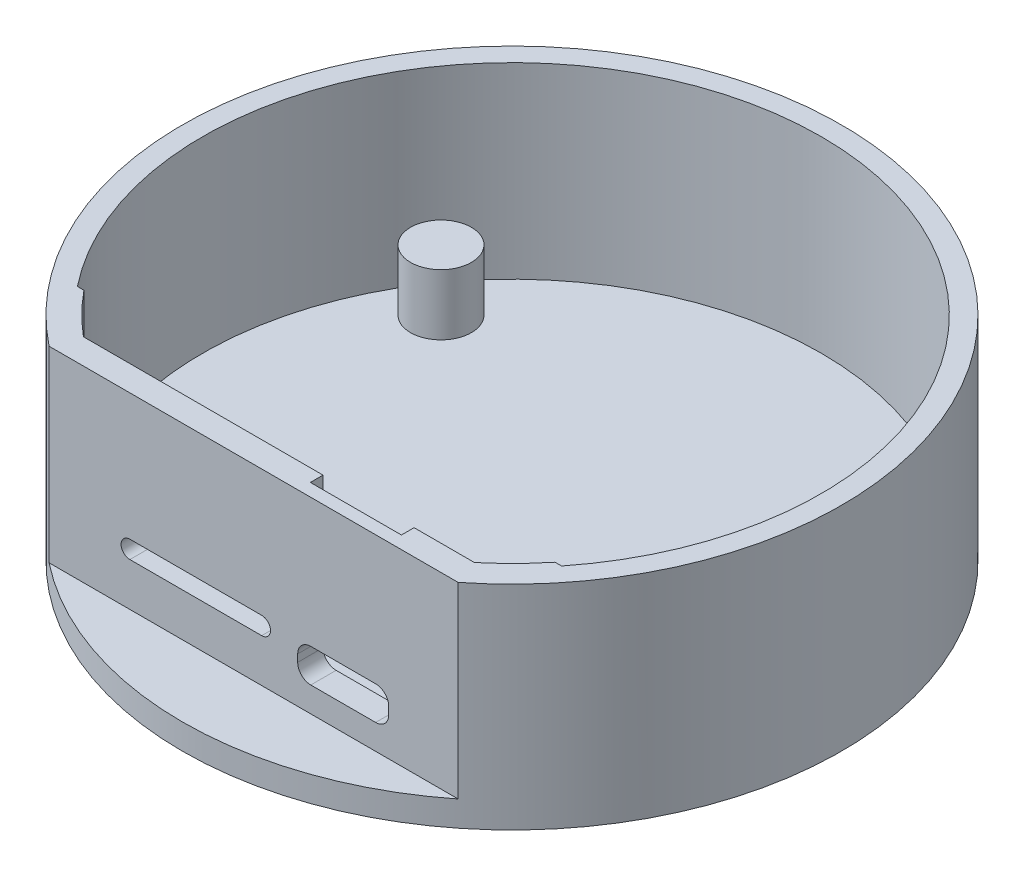
SolidWorks part; units mm, degrees
ref_plane "Front Plane" through (0, 0, 0) normal (0, 0, 1) x (1, 0, 0)
ref_plane "Top Plane" through (0, 0, 0) normal (0, 1, 0) x (1, 0, 0)
ref_plane "Right Plane" through (0, 0, 0) normal (1, 0, 0) x (0, 0, -1)
sketch "Sketch1" plane through (0, 0, 0) normal (0, 1, 0) x (1, 0, 0)
  circle A0 centre (0, 0) radius 32.5
  dimension "D1" = 65
extrude "Boss-Extrude1" add sketch "Sketch1" along normal blind 21
shell "Shell1" thickness 2.5
sketch "Sketch4" plane through (0, 21, 0) normal (0, 1, 0) x (1, 0, 0)
  line L0 (-19.2835, -22.9814) -> (19.2835, -22.9814)
  line L1 (-19.2835, -22.9814) -> (-22.9805, -22.9814)
  line L2 (19.2835, -22.9814) -> (22.9805, -22.9814)
  circle A0 centre (0, 0) radius 30 construction
  circle A1 centre (0, 0) radius 32.5 construction
  arc A2 (-22.9805, -22.9814) -> (22.9805, -22.9814) centre (0, 0) ccw
  dimension "D1" = 38.567
extrude "Cut-Extrude2" cut sketch "Sketch4" against normal up to surface (18.5 mm away) up to face at (0, 2.5, 30)
sketch "Sketch5" plane through (0, 2.5, 0) normal (0, 1, 0) x (1, 0, 0)
  line L4 (-22.9805, -22.9814) -> (22.9805, -22.9814)
  line L5 (-20.1729, -25.4814) -> (20.1729, -25.4814)
  arc A1 (-22.9805, -22.9814) -> (-20.1729, -25.4814) centre (0, 0) ccw
  arc A2 (-22.9805, -22.9814) -> (22.9805, -22.9814) centre (0, 0) ccw construction
  arc A3 (20.1729, -25.4814) -> (22.9805, -22.9814) centre (0, 0) ccw
  dimension "D1" = 2.5
extrude "Boss-Extrude2" add sketch "Sketch5" along normal through all
sketch "Sketch7" plane through (0, 21, 0) normal (0, 1, 0) x (1, 0, 0)
  line L0 (19.2835, -22.9814) -> (-19.2835, -22.9814) construction
  line L1 (-23.2315, -18.9814) -> (-23.8737, -18.9814)
  line L2 (23.2315, -18.9814) -> (23.8737, -18.9814)
  line L3 (-23.2315, -18.9814) -> (23.2315, -18.9814)
  arc A0 (23.8737, -18.9814) -> (-23.8737, -18.9814) centre (0, 0) ccw
  arc A3 (19.2835, -22.9814) -> (-19.2835, -22.9814) centre (0, 0) ccw construction
  arc A4 (19.2835, -22.9814) -> (-19.2835, -22.9814) centre (0, 0) ccw construction
  dimension "D1" = 0.5
  dimension "D2" = 4
extrude "Cut-Extrude4" cut sketch "Sketch7" against normal up to surface (18.5 mm away) up to face at (0, 2.5, -3.5093)
sketch "Sketch9" plane through (0, 2.5, 0) normal (0, 1, 0) x (1, 0, 0)
  circle A0 centre (-22, 15) radius 3
  circle A1 centre (22, 15) radius 3
  circle A2 centre (-17, -19) radius 3
  point P6 (-17.2497, 16.5169)
  point P7 (0, 0)
  point P8 (0, 0)
  point P10 (0, 0)
  point P11 (22, 15)
  point P12 (-20.8575, 14.713)
  point P15 (1.5784, -2.0857)
  dimension "D6" = 6
  dimension "D1" = 22
  dimension "D2" = 15
  dimension "D3" = 22
  dimension "D4" = 19
  dimension "D5" = 17
extrude "Boss-Extrude3" add sketch "Sketch9" along normal blind 6
sketch "Sketch6" plane through (0, 0, 25.4814) normal (0, 0, 1) x (1, 0, 0)
  line L0 (-12.2, 7.6323) -> (0.8, 7.6323) construction
  line L1 (-12.2, 8.5) -> (0.8, 8.5)
  line L2 (-12.2, 6.7646) -> (0.8, 6.7646)
  line L4 (-14, 8.5) -> (-20, 8.5) construction
  line L5 (5.64, 4.97) -> (12.04, 4.97)
  line L6 (4.35, 6.26) -> (4.35, 6.98)
  line L7 (5.64, 8.27) -> (12.04, 8.27)
  line L8 (13.33, 6.26) -> (13.33, 6.98)
  line L9 (-14, 8.5) -> (-20, 8.5) construction
  arc A0 (-12.2, 8.5) -> (-12.2, 6.7646) centre (-12.2, 7.6323) ccw
  arc A1 (0.8, 6.7646) -> (0.8, 8.5) centre (0.8, 7.6323) ccw
  arc A2 (12.04, 8.27) -> (13.33, 6.98) centre (12.04, 6.98) cw
  arc A3 (12.04, 4.97) -> (13.33, 6.26) centre (12.04, 6.26) ccw
  arc A4 (4.35, 6.98) -> (5.64, 8.27) centre (5.64, 6.98) cw
  arc A5 (5.64, 4.97) -> (4.35, 6.26) centre (5.64, 6.26) cw
  point P2 (-5.7, 7.6323)
  point P7 (4.35, 6.62)
  point P8 (8.84, 8.27)
  point P12 (13.33, 8.27)
  point P21 (4.35, 8.27)
  point P24 (4.35, 4.97)
  dimension "D4" = 13
  dimension "D9" = 1.29
  dimension "D1" = 5.7
  dimension "D2" = 1.88
  dimension "D3" = 1.7354
  dimension "D5" = 8.98
  dimension "D6" = 3.3
  dimension "D7" = 8.84
extrude "Cut-Extrude3" cut sketch "Sketch6" against normal up to next
sketch "Sketch8" plane through (0, 0, 22.9814) normal (0, 0, -1) x (-1, 0, 0)
  line L0 (-19.2835, 21) -> (19.2835, 21) construction
  line L1 (-13.33, 6.26) -> (-4.35, 6.26)
  line L2 (-13.33, 6.26) -> (-13.33, 21)
  line L3 (-13.33, 21) -> (-4.35, 21)
  line L4 (-4.35, 6.26) -> (-4.35, 21)
  line L5 (-4.35, 6.26) -> (-4.35, 6.98) construction
extrude "Cut-Extrude5" cut sketch "Sketch8" against normal blind 1.25
